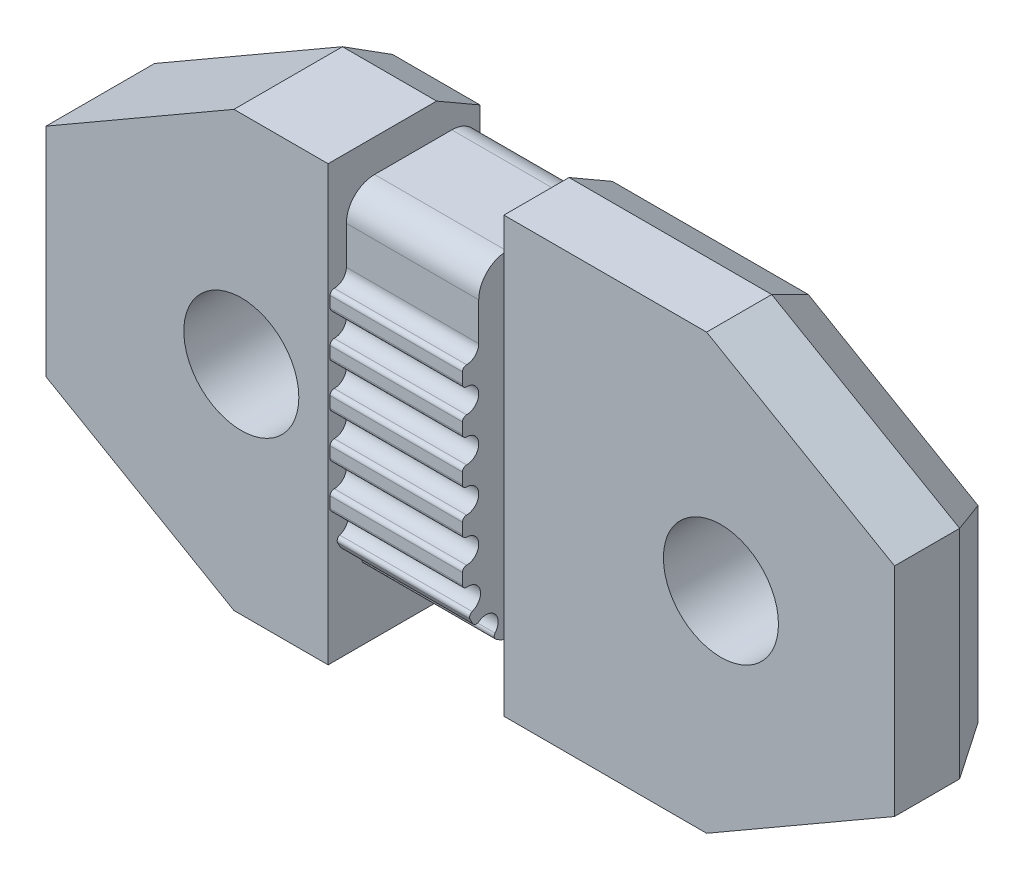
SolidWorks part; units mm, degrees
material "ABS"
ref_plane "Ebene vorne" through (0, 0, 0) normal (0, 0, 1) x (1, 0, 0)
ref_plane "Ebene oben" through (0, 0, 0) normal (0, 1, 0) x (1, 0, 0)
ref_plane "Ebene rechts" through (0, 0, 0) normal (1, 0, 0) x (0, 0, -1)
sketch "Skizze1" plane through (0, 0, 0) normal (0, 0, 1) x (1, 0, 0)
  line L0 (0, 0) -> (0, 15)
  line L1 (-10.615, 3.565) -> (-7.4598, 1.9054) construction
  line L2 (-8.7123, 0.5502) -> (-10.615, 3.565) construction
  line L3 (-7.3231, 2.8205) -> (-10.615, 3.565) construction
  line L4 (-8.1364, 1.2743) -> (-10.615, 3.565) construction
  line L5 (-9.7799, 0.8767) -> (-10.615, 3.565) construction
  line L6 (-7.05, 8.0688) -> (-7.05, 7.5688)
  line L7 (-7.05, 10.0688) -> (-7.05, 9.5688)
  line L8 (-7.05, 6.0688) -> (-7.05, 5.5688)
  line L9 (-7.05, 4.0688) -> (-7.05, 3.565)
  line L10 (-7.24, 4.2588) -> (-7.24, 3.565) construction
  line L11 (-7.8, 4.8188) -> (-7.8, 3.565) construction
  line L12 (-10.615, 3.565) -> (-7.05, 3.565) construction
  line L13 (-10.615, 3.565) -> (-10.615, 0) construction
  line L14 (-7.05, 12.0688) -> (-7.05, 11.5688)
  line L15 (-7.24, 12.2588) -> (-9.15, 12.2588)
  line L16 (-10.615, 4) -> (-9.15, 4)
  line L17 (0, 15) -> (-6, 15)
  line L18 (-6, 15) -> (-6, 0)
  line L19 (-6, 0) -> (0, 0)
  line L20 (-10.615, 4) -> (-10.615, 0) construction
  line L21 (-9.15, 4) -> (-9.15, 12.2588)
  line L22 (-10.615, 0) -> (-10.8638, 0)
  line L23 (-11.6138, 0.75) -> (-13.96, 0.75)
  line L24 (-13.96, 0.75) -> (-13.96, 4)
  line L25 (-13.96, 4) -> (-10.615, 4)
  line L27 (-7.05, 14.0688) -> (-7.05, 13.5688) [skipped]
  arc A0 (-8.5951, 0.6274) -> (-8.5493, 0.896) centre (-8.7028, 0.784) ccw
  arc A1 (-8.5493, 0.896) -> (-7.7918, 1.7157) centre (-8.1364, 1.2743) cw
  arc A2 (-7.7918, 1.7157) -> (-7.5276, 1.7825) centre (-7.6922, 1.8775) ccw
  arc A3 (-8.5951, 0.6274) -> (-8.8325, 0.4776) centre (-10.615, 3.565) cw
  arc A4 (-10.1606, 0.2207) -> (-10.3345, 0.0111) centre (-10.3495, 0.2005) cw
  arc A5 (-9.0947, 0.5518) -> (-10.1606, 0.2207) centre (-9.6138, 0.3419) ccw
  arc A6 (-8.8325, 0.4776) -> (-9.0947, 0.5518) centre (-8.9275, 0.6422) cw
  arc A7 (-10.3345, 0.0111) -> (-10.615, 0) centre (-10.615, 3.565) cw
  arc A8 (-7.24, 7.3788) -> (-7.24, 6.2588) centre (-7.24, 6.8188) ccw
  arc A9 (-7.24, 7.3788) -> (-7.05, 7.5688) centre (-7.24, 7.5688) ccw
  arc A10 (-7.05, 8.0688) -> (-7.24, 8.2588) centre (-7.24, 8.0688) ccw
  arc A11 (-7.24, 9.3788) -> (-7.24, 8.2588) centre (-7.24, 8.8188) ccw
  arc A12 (-7.24, 9.3788) -> (-7.05, 9.5688) centre (-7.24, 9.5688) ccw
  arc A13 (-7.05, 6.0688) -> (-7.24, 6.2588) centre (-7.24, 6.0688) ccw
  arc A14 (-7.24, 5.3788) -> (-7.05, 5.5688) centre (-7.24, 5.5688) ccw
  arc A15 (-7.24, 5.3788) -> (-7.24, 4.2588) centre (-7.24, 4.8188) ccw
  arc A16 (-7.05, 4.0688) -> (-7.24, 4.2588) centre (-7.24, 4.0688) ccw
  arc A17 (-7.24, 3.565) -> (-10.615, 0.19) centre (-10.615, 3.565) cw construction
  arc A18 (-7.8, 3.565) -> (-10.615, 0.75) centre (-10.615, 3.565) cw construction
  arc A19 (-7.05, 3.565) -> (-7.2453, 3.3751) centre (-7.24, 3.565) cw
  arc A20 (-7.2453, 3.3751) -> (-7.4916, 2.2864) centre (-7.3231, 2.8205) ccw
  arc A21 (-7.4916, 2.2864) -> (-7.3969, 2.0309) centre (-7.5685, 2.1127) cw
  arc A22 (-7.3969, 2.0309) -> (-7.5276, 1.7825) centre (-10.615, 3.565) cw
  arc A23 (-7.05, 10.0688) -> (-7.24, 10.2588) centre (-7.24, 10.0688) ccw
  arc A24 (-7.24, 11.3788) -> (-7.24, 10.2588) centre (-7.24, 10.8188) ccw
  arc A25 (-7.24, 11.3788) -> (-7.05, 11.5688) centre (-7.24, 11.5688) ccw
  arc A26 (-7.05, 12.0688) -> (-7.24, 12.2588) centre (-7.24, 12.0688) ccw
  arc A27 (-10.8638, 0) -> (-11.0538, 0.19) centre (-10.8638, 0.19) cw
  arc A28 (-11.0538, 0.19) -> (-11.6138, 0.75) centre (-11.6138, 0.19) ccw
  arc A33 (-7.05, 3.565) -> (-10.615, 0) centre (-10.615, 3.565) cw construction
  arc A50 (-7.24, 13.3788) -> (-7.24, 12.2588) centre (-7.24, 12.8188) ccw [skipped]
  arc A51 (-7.24, 13.3788) -> (-7.05, 13.5688) centre (-7.24, 13.5688) ccw [skipped]
  arc A52 (-7.05, 14.0688) -> (-7.24, 14.2588) centre (-7.24, 14.0688) ccw [skipped]
  point P59 (-7.8693, 2.944)
  dimension "D3" = 2
  dimension "D9" = 3.565
  dimension "D11" = 0.56
  dimension "D13" = 3.375
  dimension "D2" = 15
  dimension "D5" = 30
  dimension "D6" = 1.8
  dimension "D7" = 6
  dimension "D8" = 30
  dimension "D10" = 2
  dimension "D4" = 0.75
  dimension "D12" = 5
  dimension "D14" = 4
  dimension "D15" = 2.1
  dimension "D16" = 2
  dimension "D17" = 4.81
extrude "Aufsatz-Linear austragen1" add sketch "Skizze1" along normal blind 6.1
sketch "Skizze2" plane through (0, 0, 6.1) normal (0, 0, 1) x (1, 0, 0)
  line L1 (-6, 15) -> (0, 15)
  line L2 (-6, 15) -> (-6, 0)
  line L3 (-6, 0) -> (0, 0)
  line L4 (0, 15) -> (0, 0)
extrude "Schnitt-Linear austragen1" cut sketch "Skizze2" against normal up to surface (6.1 mm away) up to face at (-3, 7.5, 0)
sketch "Skizze3" plane through (-9.15, 0, 0) normal (-1, 0, 0) x (0, 0, 1)
  line L0 (6.1, 15.87) -> (0, 15.87)
  line L1 (0, -2.63) -> (-13, -2.63)
  line L2 (0, -2.63) -> (0, 17.37)
  line L3 (0, 17.37) -> (-13, 17.37)
  line L4 (-13, -2.63) -> (-13, 17.37)
  line L6 (-4, 7.37) -> (0, 7.37) construction
  line L9 (0, 17.37) -> (0, 12.2588)
  line L10 (0, 12.2588) -> (6.1, 12.2588)
  line L11 (6.1, 15.87) -> (6.1, 12.2588)
  line L18 (0, 4) -> (0, 12.2588) construction
  line L19 (6.1, 0) -> (0, 0) construction
  line L20 (6.1, 4) -> (6.1, 12.2588) construction
  line L21 (6.1, 12.2588) -> (0, 12.2588) construction
  circle A0 centre (-4, 7.37) radius 2.65
  dimension "D4" = 5.3
  dimension "D1" = 20
  dimension "D2" = 2.63
  dimension "D3" = 4
  dimension "D5" = 13
  dimension "D6" = 1.5
extrude "Aufsatz-Linear austragen2" add sketch "Skizze3" against normal blind 2.19
sketch "Skizze15" plane through (0, 0, 6.1) normal (0, 0, 1) x (1, 0, 0)
  line L0 (-7.8, 12.8188) -> (-7.8, 14.57)
  line L1 (-6.96, 12.2588) -> (-7.24, 12.2588) construction
  line L2 (-6.96, 12.2588) -> (-6.96, 15.87)
  line L3 (-6.96, 15.87) -> (-6.96, 12.2588) construction
  line L4 (-6.96, 15.87) -> (-9.1, 15.87)
  line L5 (-6.96, 15.87) -> (-9.15, 15.87) construction
  line L6 (-7.24, 12.2588) -> (-6.96, 12.2588)
  arc A0 (-7.8, 14.57) -> (-9.1, 15.87) centre (-9.1, 14.57) ccw
  arc A1 (-7.24, 12.2588) -> (-7.8, 12.8188) centre (-7.24, 12.8188) cw
  arc A5 (-7.24, 11.3788) -> (-7.24, 10.2588) centre (-7.24, 10.8188) ccw construction
  dimension "D1" = 1.3
extrude "Schnitt-Linear austragen7" cut sketch "Skizze15" against normal up to surface (6.1 mm away) up to face at (-7.5941, 5.4609, 0)
sketch "Skizze4" plane through (-9.15, 0, 0) normal (-1, 0, 0) x (0, 0, 1)
  line L1 (6.1, 15.87) -> (6.1, 17.37)
  line L2 (6.1, 15.87) -> (6.1, -2.63)
  line L3 (6.1, -2.63) -> (24.1, -2.63)
  line L4 (24.1, 17.37) -> (24.1, -2.63)
  line L5 (0, -2.63) -> (-13, -2.63) construction
  line L7 (6.1, 4) -> (6.1, 15.87) construction
  line L8 (-4, 7.37) -> (16.1, 7.37) construction
  line L9 (6.1, 17.37) -> (24.1, 17.37)
  line L18 (6.1, 15.87) -> (0, 15.87)
  line L19 (6.1, 15.87) -> (0, 15.87)
  line L20 (0, 15.87) -> (0, 17.37)
  line L21 (0, 15.87) -> (0, 17.37)
  line L22 (0, 17.37) -> (-13, 17.37)
  line L23 (6.1, 4) -> (6.1, 15.87)
  line L24 (0, 17.37) -> (-13, 17.37)
  line L25 (-13, 17.37) -> (-13, -2.63)
  line L26 (-13, -2.63) -> (0, -2.63)
  line L27 (0, -2.63) -> (0, 0.6557)
  line L28 (0, 0.6557) -> (0, 4)
  line L29 (0, 4) -> (6.1, 4)
  line L34 (6.1, 4) -> (6.1, 15.87)
  line L36 (-13, 17.37) -> (-13, -2.63)
  line L37 (-13, -2.63) -> (0, -2.63)
  line L38 (0, -2.63) -> (0, 0.6557)
  line L39 (0, 0.6557) -> (0, 4)
  line L40 (0, 4) -> (6.1, 4)
  circle A0 centre (-4, 7.37) radius 2.65 construction
  circle A1 centre (-4, 7.37) radius 2.65 construction
  circle A2 centre (16.1, 7.37) radius 2.65
  dimension "D2" = 10
  dimension "D3" = 8
  dimension "D1" = 0
extrude "Aufsatz-Linear austragen3" add sketch "Skizze4" along normal up to surface (4.81 mm away)
sketch "Skizze5" plane through (-9.15, 0, 0) normal (1, 0, 0) x (0, 0, -1)
  line L6 (-6.1, 17.37) -> (-24.1, 17.37)
  line L7 (-6.1, 0.6557) -> (-6.1, 15.87)
  line L8 (-6.1, 17.37) -> (-24.1, 17.37)
  line L9 (-24.1, 17.37) -> (-24.1, -2.63)
  line L10 (-24.1, -2.63) -> (-6.1, -2.63)
  line L11 (-6.1, 15.87) -> (-6.1, 17.37)
  line L12 (-6.1, -2.63) -> (-6.1, 0.6557)
  line L13 (-6.1, 15.87) -> (-6.1, 17.37)
  line L14 (-6.1, 0.6557) -> (-6.1, 15.87)
  line L15 (-6.1, -2.63) -> (-6.1, 0.6557)
  line L16 (-24.1, 17.37) -> (-24.1, -2.63)
  line L17 (-24.1, -2.63) -> (-6.1, -2.63)
  circle A0 centre (-16.1, 7.37) radius 2.65 construction
  circle A1 centre (-16.1, 7.37) radius 2.65
  dimension "D1" = 0
extrude "Aufsatz-Linear austragen4" add sketch "Skizze5" along normal offset from surface (0.19 mm away) 1.91 up to face at (-7.05, 3.8169, 3.05)
chamfer "Fase1" distance 5 angle 60 4 edges at (-11.46, -2.63, 24.1) (-10.46, -2.63, -13) (-11.46, 17.37, 24.1) (-10.46, 17.37, -13)
chamfer "Fase2" distance 2 angle 30 10 edges at (-13.96, -2.63, 10.7699) (-13.96, -0.13, 19.7699) (-13.96, 7.37, 24.1) (-13.96, -0.13, -8.6699) (-13.96, -2.63, -2.1699) (-13.96, 7.37, -13) (-13.96, 17.37, 10.7699) (-13.96, 14.87, 19.7699) (-13.96, 17.37, -2.1699) (-13.96, 14.87, -8.6699)
sketch "Skizze11" plane through (0, -2.63, 0) normal (0, -1, 0) x (1, 0, 0)
  line L0 (-13.96, 7.6) -> (-13.96, 6.1)
  line L2 (-13.96, 0) -> (-13.96, -1.5)
  line L3 (-12.46, 1.5) -> (-12.46, 4.6)
  line L4 (-10.96, 1.5) -> (-10.96, 4.6)
  arc A0 (-13.96, 6.1) -> (-12.46, 4.6) centre (-13.96, 4.6) cw
  arc A1 (-13.96, 0) -> (-12.46, 1.5) centre (-13.96, 1.5) ccw
  arc A2 (-13.96, -1.5) -> (-10.96, 1.5) centre (-13.96, 1.5) ccw
  arc A3 (-13.96, 7.6) -> (-10.96, 4.6) centre (-13.96, 4.6) cw
  dimension "D1" = 1.5
  dimension "D2" = 1.5
extrude "Schnitt-Linear austragen8" cut sketch "Skizze11" against normal blind 2 from offset 14
sketch "Skizze13" plane through (0, 0, 24.1) normal (0, 0, 1) x (1, 0, 0)
  line L0 (-13.96, 3.0367) -> (-13.96, 11.7033) construction
  line L1 (-13.96, 3.0367) -> (-13.96, 11.7033) construction
  line L2 (-13.96, 7.37) -> (-11.46, 7.37) construction
  line L3 (-12.96, 5.37) -> (-12.96, 9.37)
  line L4 (-11.46, 5.37) -> (-11.46, 9.37)
  line L5 (-13.96, 4.37) -> (-13.96, 2.87)
  line L6 (-13.96, 10.37) -> (-13.96, 11.87)
  arc A0 (-13.96, 2.87) -> (-11.46, 5.37) centre (-13.96, 5.37) ccw
  arc A1 (-13.96, 4.37) -> (-12.96, 5.37) centre (-13.96, 5.37) ccw
  arc A2 (-13.96, 10.37) -> (-12.96, 9.37) centre (-13.96, 9.37) cw
  arc A3 (-13.96, 11.87) -> (-11.46, 9.37) centre (-13.96, 9.37) cw
  point P15 (-12.96, 7.37)
  dimension "D1" = 1.5
  dimension "D2" = 1
  dimension "D3" = 6
extrude "Schnitt-Linear austragen5" cut sketch "Skizze13" against normal blind 2.5 from offset 13.5
fillet "Verrundung1" radius 1.3 1 edges at (-13.96, 15.87, 3.05)
mirror "Spiegeln1" about plane through (-6.96, -14.2821, -13) normal (0, 0, 1) of bodies 116
delete or keep bodies "Körper-Löschen1" type delete bodies bodies 116
move or copy body "Körper-Verschieben/Kopieren1" bodies to move or copy 120 copy no rotation origin (-10.55, 0, 5.55) rotation axis (0, -1, 0) rotation angle 90
